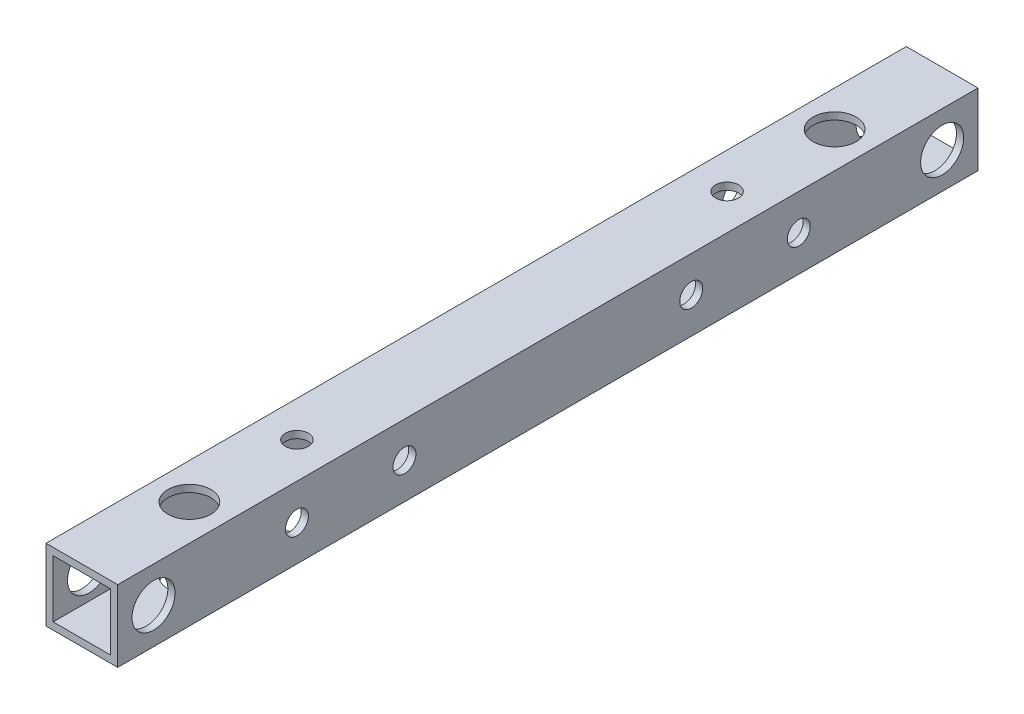
SolidWorks part; units mm, degrees
ref_plane "正面" through (0, 0, 0) normal (0, 0, 1) x (1, 0, 0)
ref_plane "平面" through (0, 0, 0) normal (0, 1, 0) x (1, 0, 0)
ref_plane "右側面" through (0, 0, 0) normal (1, 0, 0) x (0, 0, -1)
sketch "ｽｹｯﾁ1" plane through (0, 0, 0) normal (0, 0, 1) x (1, 0, 0)
  line L5 (-5, -5) -> (5, -5)
  line L6 (-5, -5) -> (-5, 5)
  line L7 (-5, 5) -> (5, 5)
  line L8 (5, -5) -> (5, 5)
  line L9 (-5, -5) -> (5, 5) construction
  line L10 (-5, 5) -> (5, -5) construction
  line L11 (4, -4) -> (-4, -4)
  line L12 (4, -4) -> (4, 4)
  line L13 (4, 4) -> (-4, 4)
  line L14 (-4, -4) -> (-4, 4)
  line L15 (4, -4) -> (-4, 4) construction
  line L16 (4, 4) -> (-4, -4) construction
  point P0 (0, 0)
  point P7 (0, 0)
  dimension "D1" = 10
  dimension "D2" = 10
  dimension "D3" = 8
extrude "ﾎﾞｽ - 押し出し1" add sketch "ｽｹｯﾁ1" along normal blind 120
sketch "ｽｹｯﾁ2" plane through (-5, 0, 0) normal (-1, 0, 0) x (0, 0, 1)
  line L0 (0, 5) -> (0, -5) construction
  line L1 (120, -5) -> (0, -5) construction
  line L2 (120, 5) -> (120, -5) construction
  circle A0 centre (5, 0) radius 3
  circle A1 centre (115, 0) radius 3
  dimension "D1" = 6
  dimension "D2" = 6
  dimension "D3" = 5
  dimension "D4" = 5
  dimension "D5" = 5
  dimension "D6" = 5
extrude "ｶｯﾄ - 押し出し1" cut sketch "ｽｹｯﾁ2" against normal through all
sketch "ｽｹｯﾁ3" plane through (0, 5, 0) normal (0, 1, 0) x (1, 0, 0)
  line L0 (5, -120) -> (-5, -120) construction
  line L1 (5, -120) -> (5, 0) construction
  line L2 (5, 0) -> (-5, 0) construction
  line L3 (-5, -120) -> (-5, 0) construction
  circle A0 centre (0, -105) radius 3
  circle A1 centre (0, -15) radius 3
  dimension "D1" = 6
  dimension "D2" = 15
  dimension "D3" = 5
  dimension "D4" = 6
  dimension "D5" = 15
  dimension "D6" = 5
extrude "ｶｯﾄ - 押し出し2" cut sketch "ｽｹｯﾁ3" against normal blind 10
sketch "ｽｹｯﾁ4" plane through (0, 5, 0) normal (0, 1, 0) x (1, 0, 0)
  line L0 (-5, -120) -> (-5, 0) construction
  circle A0 centre (0, -30) radius 1.6
  circle A1 centre (0, -90) radius 1.6
  circle A2 centre (0, -15) radius 3 construction
  circle A3 centre (0, -105) radius 3 construction
  dimension "D1" = 3.2
  dimension "D2" = 3.2
  dimension "D3" = 15
  dimension "D4" = 15
  dimension "D5" = 5
  dimension "D6" = 5
extrude "ｶｯﾄ - 押し出し3" cut sketch "ｽｹｯﾁ4" against normal blind 10
sketch "ｽｹｯﾁ5" plane through (-5, 0, 0) normal (-1, 0, 0) x (0, 0, 1)
  line L0 (120, -5) -> (0, -5) construction
  line L1 (120, 5) -> (0, 5) construction
  circle A0 centre (25, 0) radius 1.6
  circle A1 centre (95, 0) radius 1.6
  circle A2 centre (5, 0) radius 3 construction
  circle A3 centre (115, 0) radius 3 construction
  dimension "D1" = 3.2
  dimension "D2" = 20
  dimension "D3" = 5
  dimension "D4" = 3.2
  dimension "D5" = 5
  dimension "D6" = 20
extrude "ｶｯﾄ - 押し出し4" cut sketch "ｽｹｯﾁ5" against normal through all
sketch "ｽｹｯﾁ6" plane through (0, -5, 0) normal (0, -1, 0) x (-1, 0, 0)
  circle A0 centre (0, -30) radius 3
  circle A1 centre (0, -90) radius 3
  dimension "D1" = 6
  dimension "D2" = 6
extrude "ｶｯﾄ - 押し出し5" cut sketch "ｽｹｯﾁ6" against normal blind 2
sketch "ｽｹｯﾁ7" plane through (-5, 0, 0) normal (-1, 0, 0) x (0, 0, 1)
  line L0 (120, 5) -> (0, 5) construction
  line L1 (120, 5) -> (120, -5) construction
  circle A0 centre (80, 0) radius 1.6
  circle A1 centre (40, 0) radius 1.6
  dimension "D1" = 3.2
  dimension "D2" = 3.2
  dimension "D3" = 5
  dimension "D4" = 5
  dimension "D5" = 40
  dimension "D6" = 40
extrude "ｶｯﾄ - 押し出し6" cut sketch "ｽｹｯﾁ7" against normal through all
